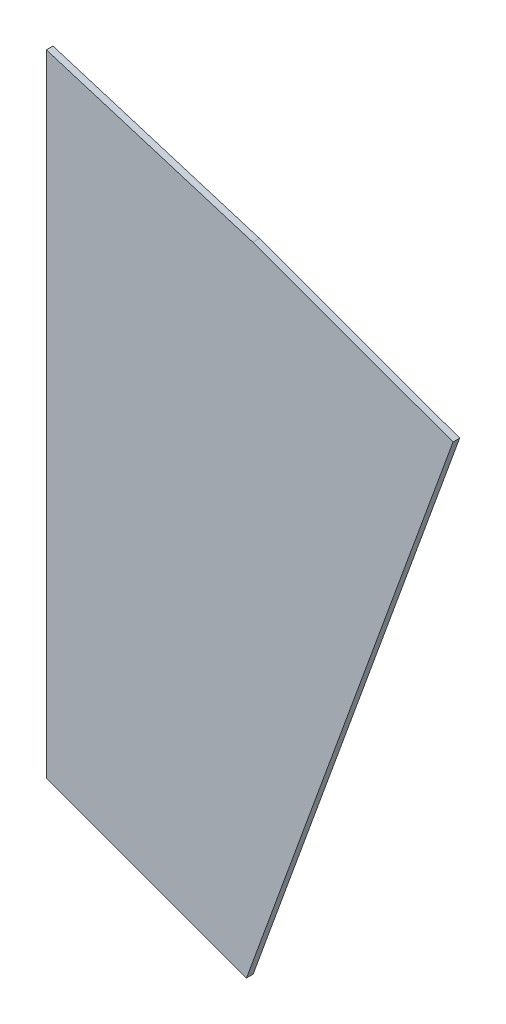
SolidWorks part; units mm, degrees
ref_plane "Front Plane" through (0, 0, 0) normal (0, 0, 1) x (1, 0, 0)
ref_plane "Top Plane" through (0, 0, 0) normal (0, 1, 0) x (1, 0, 0)
ref_plane "Right Plane" through (0, 0, 0) normal (1, 0, 0) x (0, 0, -1)
sketch "Sketch1" plane through (0, 0, 0) normal (0, 0, 1) x (1, 0, 0)
  line L0 (0, 0) -> (0, 152.4)
  line L1 (0, 0) -> (49.8963, 137.0888) construction
  line L2 (49.8963, 137.0888) -> (0, 152.4)
  line L4 (0, 0) -> (48.3556, -17.6)
  line L5 (186.8854, 363.0075) -> (-4.2355, -162.0927) construction
  line L6 (48.3556, -17.6) -> (98.2518, 119.4888)
  line L7 (98.2518, 119.4888) -> (49.8963, 137.0888)
  dimension "D1" = 152.4
  dimension "D2" = 20
extrude "Boss-Extrude1" add sketch "Sketch1" along normal blind 1.6002
